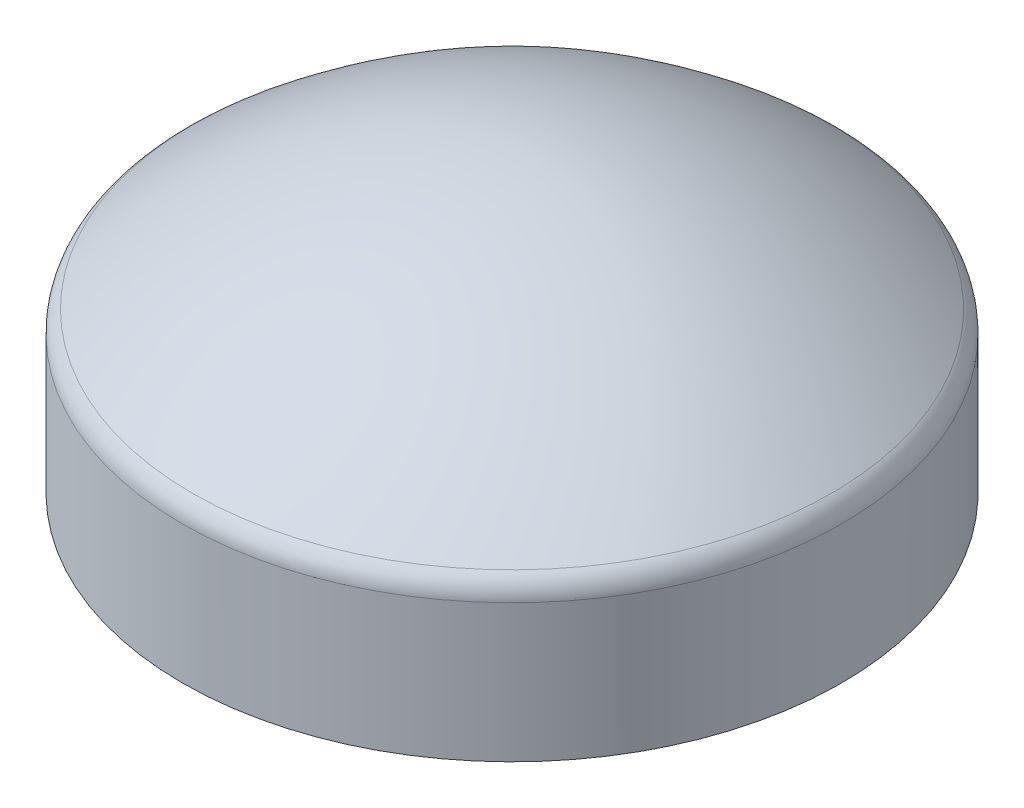
SolidWorks part; units mm, degrees
ref_plane "Front Plane" through (0, 0, 0) normal (0, 0, 1) x (1, 0, 0)
ref_plane "Top Plane" through (0, 0, 0) normal (0, 1, 0) x (1, 0, 0)
ref_plane "Right Plane" through (0, 0, 0) normal (1, 0, 0) x (0, 0, -1)
sketch "Sketch1" plane through (0, 0, 0) normal (0, 0, 1) x (1, 0, 0)
  line L1 (-24.05, 0) -> (-22.6, 0)
  line L2 (-24.05, 0) -> (-24.05, 11)
  line L8 (-22.05, 11) -> (-24.05, 11) construction
  line L9 (0, 19) -> (0, 21) construction
  line L10 (-22.6, 0) -> (-22.6, 2.4)
  line L11 (-22.6, 11) -> (-22.05, 11)
  line L14 (0, 21) -> (0, 19)
  line L15 (-22.6, 3.4) -> (-22.6, 11)
  arc A0 (-22.6, 2.4) -> (-22.6, 3.4) centre (-22.6, 2.9) cw
  spline S0 degree 2 poles (-24.05, 11) (-12.025, 21) (0, 21) knots 0 0 0 0.5 0.5 0.5
  spline S1 degree 2 poles (-22.05, 11) (-11.025, 19) (0, 19) knots 0 0 0 0.5 0.5 0.5
  dimension "D4" = 21
  dimension "D6" = 2.4
  dimension "D7" = 0.5
  dimension "D1" = 22.6
  dimension "D2" = 24.05
  dimension "D3" = 11
  dimension "D5" = 2
revolve "Revolve2" add sketch "Sketch1" angle 360 about L14
fillet "Fillet1" radius 2 1 edges at (0, 11, 24.05)
